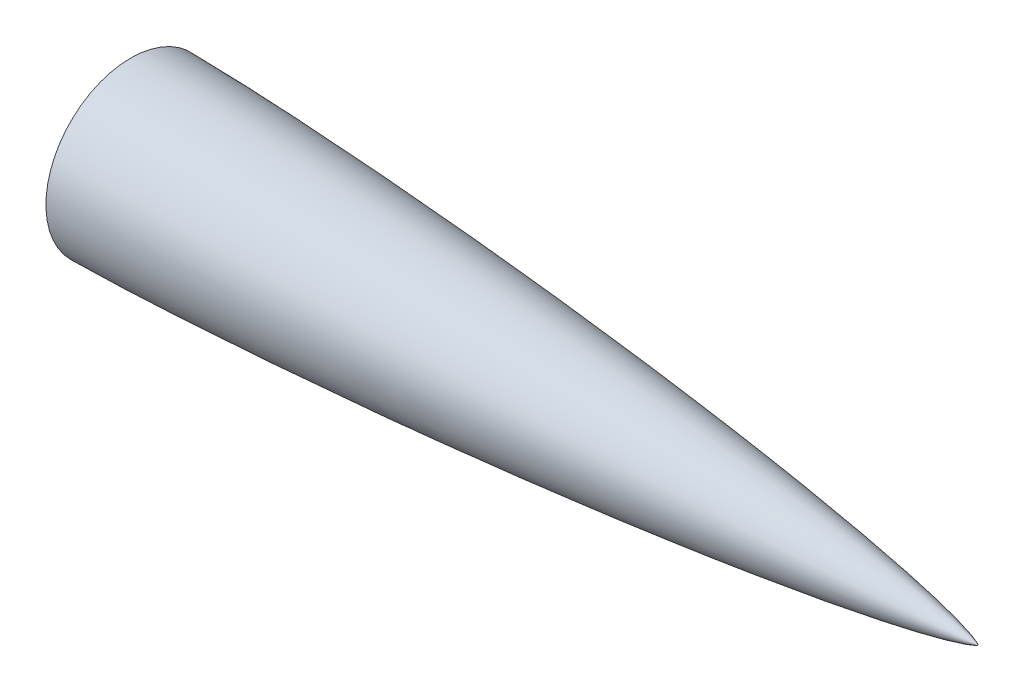
SolidWorks part; units mm, degrees
ref_plane "Front Plane" through (0, 0, 0) normal (0, 0, 1) x (1, 0, 0)
ref_plane "Top Plane" through (0, 0, 0) normal (0, 1, 0) x (1, 0, 0)
ref_plane "Right Plane" through (0, 0, 0) normal (1, 0, 0) x (0, 0, -1)
sketch "Sketch1" plane through (0, 0, 0) normal (0, 0, 1) x (1, 0, 0)
  line L0 (500, 0) -> (-49500, 0) construction
  line L1 (500, 0) -> (-500, 0)
  line L2 (-500, 100) -> (-500, 0)
  spline S0 degree 4 poles (500, 0) (499.9999, 0.0011) (499.9995, 0.0031) (499.9899, 0.0278) (499.9595, 0.0684) (499.8941, 0.1409) (499.6784, 0.3245) (499.3301, 0.5524) (498.6999, 0.9053) (497.7032, 1.3798) (496.4618, 1.9022) (494.3132, 2.7173) (491.3985, 3.6992) (487.4705, 4.897) (482.5194, 6.2695) (475.7873, 8.0005) (468.4974, 9.7226) (461.003, 11.3855) (451.6966, 13.344) (442.006, 15.2856) (430.679, 17.4418) (413.9015, 20.476) (393.2755, 23.9829) (368.7904, 27.8856) (340.4389, 32.121) (304.9585, 37.132) (262.3291, 42.761) (212.5368, 48.8719) (155.5702, 55.3371) (98.5543, 61.3507) (41.4968, 66.9552) (-15.5968, 72.1779) (-72.7226, 77.0343) (-122.7336, 80.9687) (-165.6173, 84.1143) (-201.3646, 86.5806) (-229.9689, 88.4585) (-258.5795, 90.2381) (-287.1963, 91.9152) (-315.8191, 93.4846) (-344.4479, 94.9392) (-369.5035, 96.1034) (-390.9835, 97.0155) (-408.8861, 97.7125) (-423.2097, 98.2294) (-437.4089, 98.6976) (-449.7556, 99.0624) (-460.2495, 99.3386) (-468.8899, 99.541) (-475.8025, 99.6863) (-481.8515, 99.7967) (-487.0365, 99.8778) (-491.3575, 99.9333) (-494.8144, 99.9712) (-497.4072, 99.9893) (-499.1357, 100) (-500, 100) knots 0 0 0 0 0 0.000004 0.000008 0.000104 0.0002 0.000392 0.001131 0.001755 0.003068 0.004775 0.006481 0.010883 0.015285 0.021089 0.026893 0.0385 0.045045 0.051589 0.064678 0.077767 0.090856 0.119329 0.147802 0.176276 0.204749 0.261696 0.318643 0.37559 0.432537 0.489483 0.54643 0.603377 0.660324 0.688797 0.717271 0.745744 0.774217 0.802691 0.831164 0.859637 0.888111 0.902347 0.916584 0.930821 0.945058 0.958793 0.965661 0.972529 0.979397 0.986264 0.989698 0.993132 0.996566 1 1 1 1 1 construction
  spline S1 degree 4 poles (500, 0) (499.9999, 0.0011) (499.9995, 0.0031) (499.9899, 0.0278) (499.9595, 0.0684) (499.8941, 0.1409) (499.6784, 0.3245) (499.3301, 0.5524) (498.6999, 0.9053) (497.7032, 1.3798) (496.4618, 1.9022) (494.3132, 2.7173) (491.3985, 3.6992) (487.4705, 4.897) (482.5194, 6.2695) (475.7873, 8.0005) (468.4974, 9.7226) (461.003, 11.3855) (451.6966, 13.344) (442.006, 15.2856) (430.679, 17.4418) (413.9015, 20.476) (393.2755, 23.9829) (368.7904, 27.8856) (340.4389, 32.121) (304.9585, 37.132) (262.3291, 42.761) (212.5368, 48.8719) (155.5702, 55.3371) (98.5543, 61.3507) (41.4968, 66.9552) (-15.5968, 72.1779) (-72.7226, 77.0343) (-122.7336, 80.9687) (-165.6173, 84.1143) (-201.3646, 86.5806) (-229.9689, 88.4585) (-258.5795, 90.2381) (-287.1963, 91.9152) (-315.8191, 93.4846) (-344.4479, 94.9392) (-369.5035, 96.1034) (-390.9835, 97.0155) (-408.8861, 97.7125) (-423.2097, 98.2294) (-437.4089, 98.6976) (-449.7556, 99.0624) (-460.2495, 99.3386) (-468.8899, 99.541) (-475.8025, 99.6863) (-481.8515, 99.7967) (-487.0365, 99.8778) (-491.3575, 99.9333) (-494.8144, 99.9712) (-497.4072, 99.9893) (-499.1357, 100) (-500, 100) knots 0 0 0 0 0 0.000004 0.000008 0.000104 0.0002 0.000392 0.001131 0.001755 0.003068 0.004775 0.006481 0.010883 0.015285 0.021089 0.026893 0.0385 0.045045 0.051589 0.064678 0.077767 0.090856 0.119329 0.147802 0.176276 0.204749 0.261696 0.318643 0.37559 0.432537 0.489483 0.54643 0.603377 0.660324 0.688797 0.717271 0.745744 0.774217 0.802691 0.831164 0.859637 0.888111 0.902347 0.916584 0.930821 0.945058 0.958793 0.965661 0.972529 0.979397 0.986264 0.989698 0.993132 0.996566 1 1 1 1 1
sketch "Sketch7" plane through (0, 0, 0) normal (0, 0, 1) x (1, 0, 0)
  line L0 (-500, 100) -> (-500, -2.5864)
revolve "Revolve2" add sketch "Sketch1" angle 360 about L0
